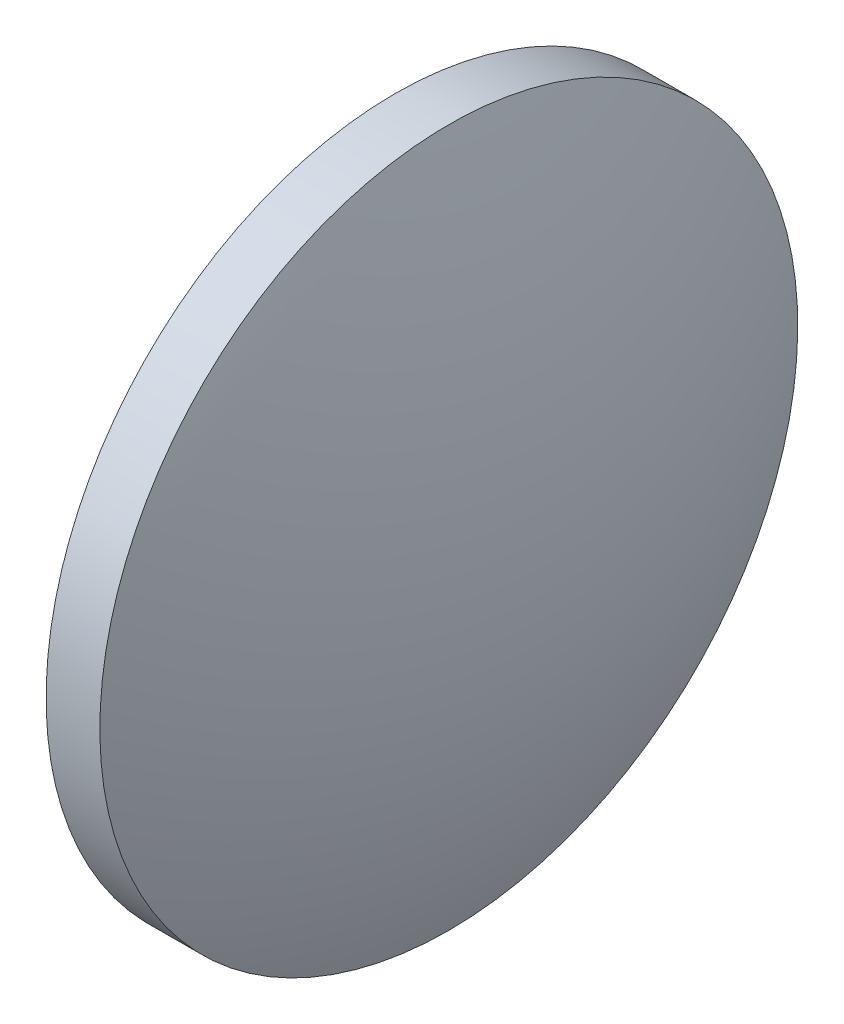
SolidWorks part; units mm, degrees
ref_plane "前视基准面" through (0, 0, 0) normal (0, 0, 1) x (1, 0, 0)
ref_plane "上视基准面" through (0, 0, 0) normal (0, 1, 0) x (1, 0, 0)
ref_plane "右视基准面" through (0, 0, 0) normal (1, 0, 0) x (0, 0, -1)
sketch "草图1" plane through (0, 0, 0) normal (0, 0, 1) x (1, 0, 0)
  line L0 (-0.8287, 0) -> (0.8287, 0)
  line L1 (0.2311, 3) -> (-0.2311, 3)
  line L2 (0, 3) -> (0, 0) construction
  line L3 (-0.8287, 0) -> (-0.8287, -1.1057) construction
  arc A0 (0.8287, 0) -> (0.2311, 3) centre (-7.0002, 0) ccw
  arc A1 (-0.8287, 0) -> (-0.2311, 3) centre (7.0002, 0) cw
  dimension "D1" = 3
revolve "旋转1" add sketch "草图1" angle 360 about L0
